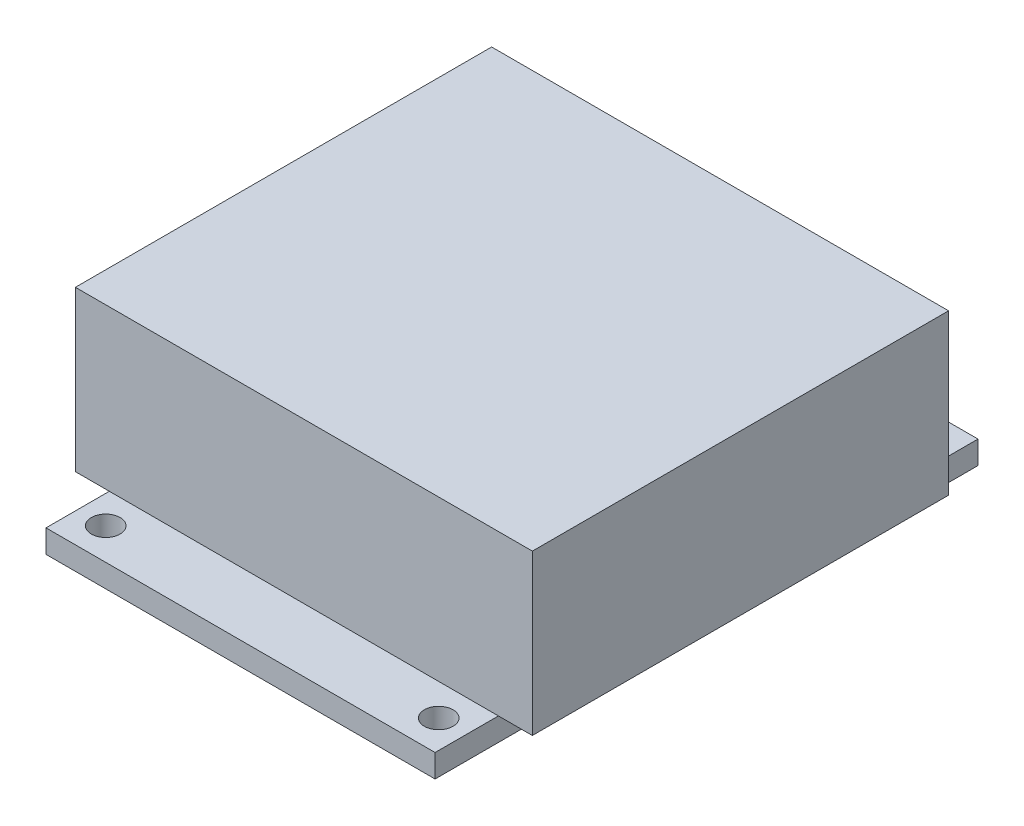
SolidWorks part; units mm, degrees
ref_plane "Front Plane" through (0, 0, 0) normal (0, 0, 1) x (1, 0, 0)
ref_plane "Top Plane" through (0, 0, 0) normal (0, 1, 0) x (1, 0, 0)
ref_plane "Right Plane" through (0, 0, 0) normal (1, 0, 0) x (0, 0, -1)
sketch "Sketch1" plane through (0, 0, 0) normal (0, 1, 0) x (1, 0, 0)
  line L1 (21.5, -30) -> (-21.5, -30)
  line L2 (21.5, -30) -> (21.5, 30)
  line L3 (21.5, 30) -> (-21.5, 30)
  line L4 (-21.5, -30) -> (-21.5, 30)
  line L5 (21.5, -30) -> (-21.5, 30) construction
  line L6 (21.5, 30) -> (-21.5, -30) construction
  line L7 (18.4, -26.5) -> (-18.4, -26.5) construction
  line L8 (18.4, -26.5) -> (18.4, 26.5) construction
  line L9 (18.4, 26.5) -> (-18.4, 26.5) construction
  line L10 (-18.4, -26.5) -> (-18.4, 26.5) construction
  line L11 (18.4, -26.5) -> (-18.4, 26.5) construction
  line L12 (18.4, 26.5) -> (-18.4, -26.5) construction
  circle A0 centre (-18.4, 26.5) radius 1.5875
  circle A1 centre (18.4, 26.5) radius 1.5875
  circle A2 centre (18.4, -26.5) radius 1.5875
  circle A3 centre (-18.4, -26.5) radius 1.5875
  point P0 (0, 0)
  point P6 (0, 0)
  dimension "D5" = 3.175
  dimension "D1" = 43
  dimension "D2" = 60
  dimension "D3" = 36.8
  dimension "D4" = 53
extrude "Boss-Extrude1" add sketch "Sketch1" along normal blind 2.54 contours L4 L3 L2 L1
sketch "Sketch2" plane through (0, 2.54, 0) normal (0, 1, 0) x (1, 0, 0)
  line L1 (25.25, -23) -> (-25.25, -23)
  line L2 (25.25, -23) -> (25.25, 23)
  line L3 (25.25, 23) -> (-25.25, 23)
  line L4 (-25.25, -23) -> (-25.25, 23)
  line L5 (25.25, -23) -> (-25.25, 23) construction
  line L6 (25.25, 23) -> (-25.25, -23) construction
  point P0 (0, 0)
  dimension "D1" = 50.5
  dimension "D2" = 46
extrude "Boss-Extrude2" add sketch "Sketch2" along normal blind 17.65
